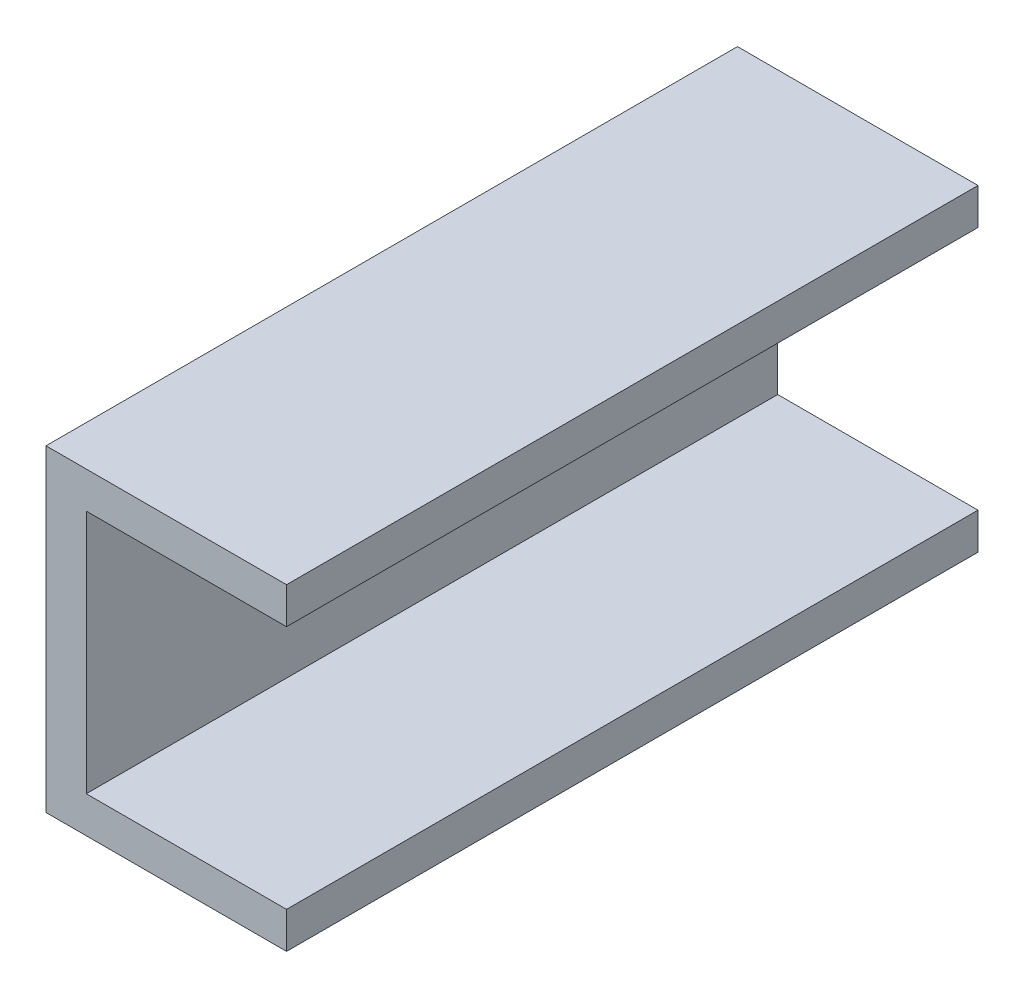
SolidWorks part; units mm, degrees
ref_plane "Front Plane" through (0, 0, 0) normal (0, 0, 1) x (1, 0, 0)
ref_plane "Top Plane" through (0, 0, 0) normal (0, 1, 0) x (1, 0, 0)
ref_plane "Right Plane" through (0, 0, 0) normal (1, 0, 0) x (0, 0, -1)
sketch "Sketch1" plane through (0, 0, 0) normal (0, 0, 1) x (1, 0, 0)
  line L0 (0, 35) -> (0, -35)
  line L1 (0, -35) -> (53.0172, -35)
  line L2 (53.0172, -35) -> (53.0172, -26.9745)
  line L3 (53.0172, -26.9745) -> (8.877, -26.9745)
  line L4 (8.877, -26.9745) -> (8.877, 26.9745)
  line L5 (8.877, 26.9745) -> (53.0172, 26.9745)
  line L6 (53.0172, 26.9745) -> (53.0172, 35)
  line L7 (53.0172, 35) -> (0, 35)
  point P4 (0, 0)
  dimension "D1" = 70
extrude "Boss-Extrude1" add sketch "Sketch1" along normal blind 152.4
